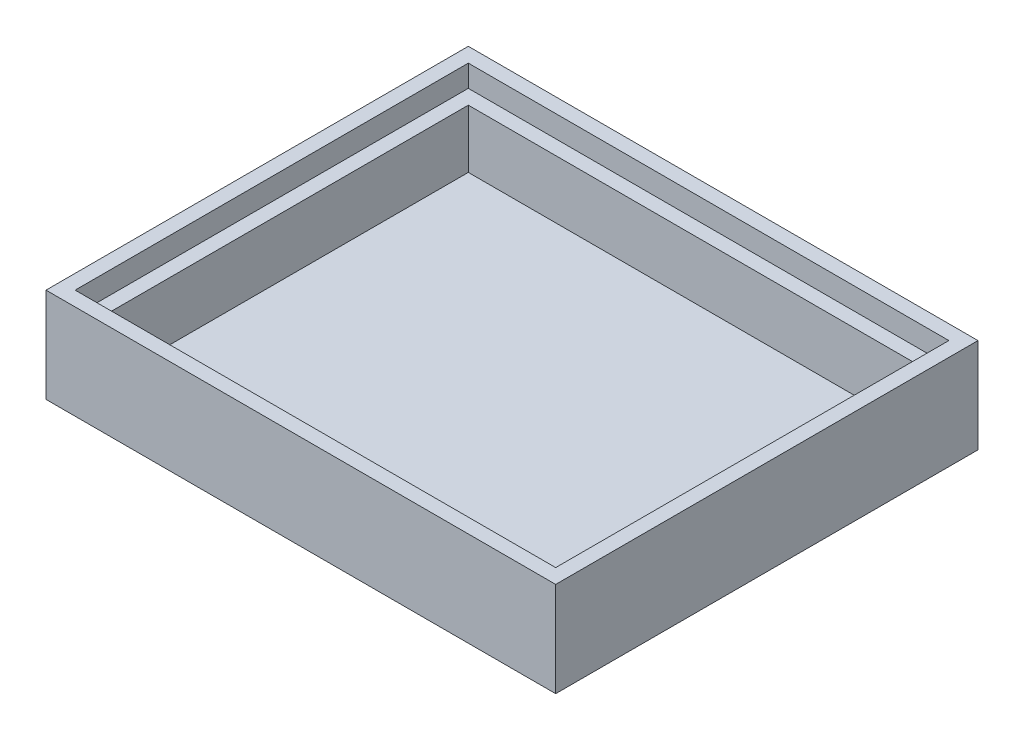
SolidWorks part; units mm, degrees
ref_plane "Płaszczyzna przednia" through (0, 0, 0) normal (0, 0, 1) x (1, 0, 0)
ref_plane "Płaszczyzna górna" through (0, 0, 0) normal (0, 1, 0) x (1, 0, 0)
ref_plane "Płaszczyzna prawa" through (0, 0, 0) normal (1, 0, 0) x (0, 0, -1)
sketch "Szkic1" plane through (0, 0, 0) normal (0, 1, 0) x (1, 0, 0)
  line L1 (0, 0) -> (70, 0)
  line L2 (0, 0) -> (0, 58)
  line L3 (0, 58) -> (70, 58)
  line L4 (70, 0) -> (70, 58)
  dimension "D1" = 58
  dimension "D2" = 70
extrude "Dodanie-wyciągnięcie1" add sketch "Szkic1" along normal blind 2
sketch "Szkic2" plane through (0, 2, 0) normal (0, 1, 0) x (1, 0, 0)
  line L1 (0, 58) -> (70, 58)
  line L2 (0, 58) -> (0, 0)
  line L3 (0, 0) -> (70, 0)
  line L4 (70, 58) -> (70, 0)
  line L5 (4, 54) -> (66, 54)
  line L6 (4, 54) -> (4, 4)
  line L7 (4, 4) -> (66, 4)
  line L8 (66, 54) -> (66, 4)
  dimension "D1" = 4
  dimension "D2" = 4
  dimension "D3" = 4
  dimension "D4" = 4
extrude "Dodanie-wyciągnięcie2" add sketch "Szkic2" along normal blind 8
sketch "Szkic3" plane through (0, 10, 0) normal (0, 1, 0) x (1, 0, 0)
  line L1 (2, 56) -> (68, 56)
  line L2 (2, 56) -> (2, 2)
  line L3 (2, 2) -> (68, 2)
  line L4 (0, 58) -> (0, 0)
  line L5 (0, 0) -> (70, 0)
  line L6 (70, 0) -> (70, 58)
  line L7 (70, 58) -> (0, 58)
  line L8 (0, 58) -> (0, 0)
  line L9 (0, 0) -> (70, 0)
  line L10 (70, 0) -> (70, 58)
  line L11 (70, 58) -> (0, 58)
  line L12 (68, 56) -> (68, 2)
  dimension "D2" = 2
  dimension "D3" = 2
  dimension "D4" = 2
  dimension "D5" = 2
  dimension "D1" = 0
extrude "Dodanie-wyciągnięcie3" add sketch "Szkic3" along normal blind 3
